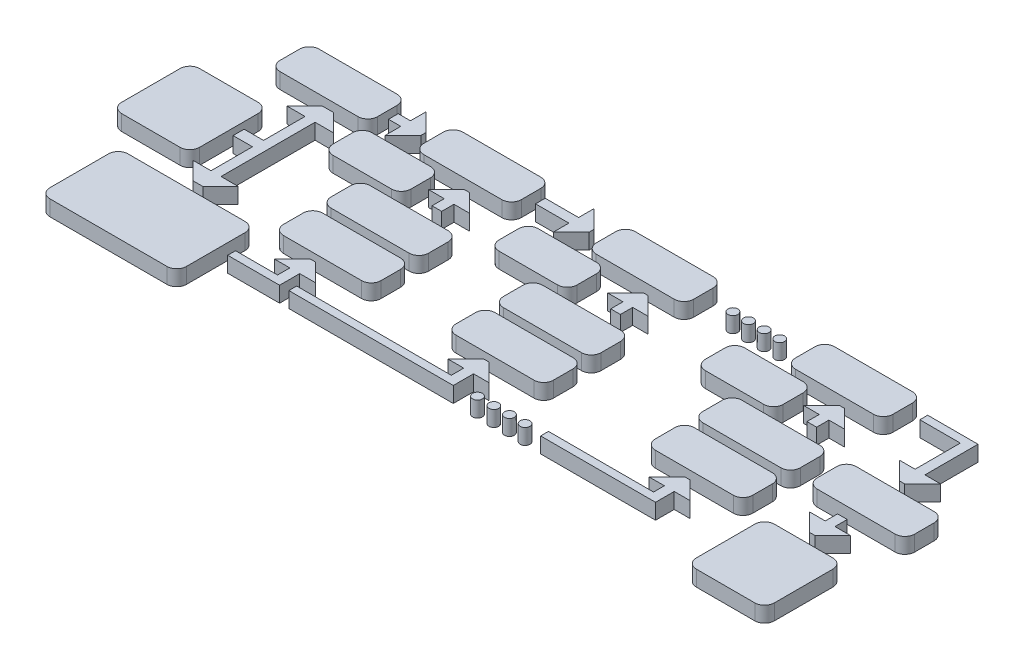
SolidWorks part; units mm, degrees
ref_plane "Front Plane" through (0, 0, 0) normal (0, 0, 1) x (1, 0, 0)
ref_plane "Top Plane" through (0, 0, 0) normal (0, 1, 0) x (1, 0, 0)
ref_plane "Right Plane" through (0, 0, 0) normal (1, 0, 0) x (0, 0, -1)
sketch "Sketch2" plane through (0, 0, 0) normal (0, 1, 0) x (1, 0, 0)
  line L0 (229.7637, 216.3988) -> (1504.4304, 216.3988) construction
  line L1 (-69.85, 25.4) -> (69.85, 25.4) construction
  line L2 (-69.85, 25.4) -> (-69.85, -25.4) construction
  line L3 (-69.85, -25.4) -> (69.85, -25.4) construction
  line L4 (69.85, 25.4) -> (69.85, -25.4) construction
  point P0 (0, 0)
  dimension "D1" = 50.8
  dimension "D2" = 139.7
sketch "Sketch3" plane through (0, 0, 0) normal (0, 1, 0) x (1, 0, 0)
  line L0 (-7.1378, 13.5425) -> (5.5622, 13.5425)
  line L1 (-58.6316, 13.5425) -> (-45.9316, 13.5425)
  line L2 (-60.2191, 15.13) -> (-60.2191, 18.305)
  line L3 (-58.6316, 19.8925) -> (-45.9316, 19.8925)
  line L4 (-44.3441, 15.13) -> (-44.3441, 18.305)
  line L5 (-8.7253, 15.13) -> (-8.7253, 18.305)
  line L6 (-7.1378, 19.8925) -> (5.5622, 19.8925)
  line L7 (7.1497, 15.13) -> (7.1497, 18.305)
  line L8 (-35.2189, 13.5425) -> (-22.5189, 13.5425)
  line L9 (-36.8064, 15.13) -> (-36.8064, 18.305)
  line L10 (-35.2189, 19.8925) -> (-22.5189, 19.8925)
  line L11 (-20.9314, 15.13) -> (-20.9314, 18.305)
  line L12 (-35.2189, -1.5522) -> (-22.5189, -1.5522)
  line L13 (-36.8064, 0.0353) -> (-36.8064, 3.2103)
  line L14 (-35.2189, 4.7978) -> (-22.5189, 4.7978)
  line L15 (-20.9314, 0.0353) -> (-20.9314, 3.2103)
  line L16 (25.3178, 13.5425) -> (38.0178, 13.5425)
  line L17 (23.7303, 15.13) -> (23.7303, 18.305)
  line L18 (25.3178, 19.8925) -> (38.0178, 19.8925)
  line L19 (39.6053, 15.13) -> (39.6053, 18.305)
  line L20 (-7.1378, -1.5522) -> (5.5622, -1.5522)
  line L21 (-8.7253, 0.0353) -> (-8.7253, 3.2103)
  line L22 (-7.1378, 4.7978) -> (5.5622, 4.7978)
  line L23 (7.1497, 0.0353) -> (7.1497, 3.2103)
  line L24 (25.3178, -1.5522) -> (38.0178, -1.5522)
  line L25 (23.7303, 0.0353) -> (23.7303, 3.2103)
  line L26 (25.3178, 4.7978) -> (38.0178, 4.7978)
  line L27 (39.6053, 0.0353) -> (39.6053, 3.2103)
  line L28 (43.9892, -1.5958) -> (56.6892, -1.5958)
  line L29 (42.4017, -0.0083) -> (42.4017, 3.1667)
  line L30 (43.9892, 4.7542) -> (56.6892, 4.7542)
  line L31 (58.2767, -0.0083) -> (58.2767, 3.1667)
  line L32 (-35.2189, -9.2939) -> (-22.5189, -9.2939)
  line L33 (-36.8064, -7.7064) -> (-36.8064, -4.5314)
  line L34 (-35.2189, -2.9439) -> (-22.5189, -2.9439)
  line L35 (-20.9314, -7.7064) -> (-20.9314, -4.5314)
  line L36 (-7.1378, -9.2939) -> (5.5622, -9.2939)
  line L37 (-8.7253, -7.7064) -> (-8.7253, -4.5314)
  line L38 (-7.1378, -2.9439) -> (5.5622, -2.9439)
  line L39 (7.1497, -7.7064) -> (7.1497, -4.5314)
  line L40 (25.3178, -9.2939) -> (38.0178, -9.2939)
  line L41 (23.7303, -7.7064) -> (23.7303, -4.5314)
  line L42 (25.3178, -2.9439) -> (38.0178, -2.9439)
  line L43 (39.6053, -7.7064) -> (39.6053, -4.5314)
  line L44 (-42.5202, 6.0577) -> (-32.9952, 6.0577)
  line L45 (-40.3627, -23.1396) -> (-59.4127, -23.1396)
  line L46 (-38.7752, -21.5521) -> (-38.7752, -12.0271)
  line L47 (-40.3627, -10.4396) -> (-59.4127, -10.4396)
  line L48 (-61.0002, -21.5521) -> (-61.0002, -12.0271)
  line L49 (-15.4735, 6.0577) -> (-5.9485, 6.0577)
  line L50 (-17.061, 7.6452) -> (-17.061, 10.8202)
  line L51 (-15.4735, 12.4077) -> (-5.9485, 12.4077)
  line L52 (-4.361, 7.6452) -> (-4.361, 10.8202)
  line L53 (-44.1077, 7.6452) -> (-44.1077, 10.8202)
  line L54 (-42.5202, 12.4077) -> (-32.9952, 12.4077)
  line L55 (-31.4077, 7.6452) -> (-31.4077, 10.8202)
  line L56 (18.1587, 6.0027) -> (27.6837, 6.0027)
  line L57 (16.5712, 7.5902) -> (16.5712, 10.8202)
  line L58 (18.1587, 12.4077) -> (27.6837, 12.4077)
  line L59 (29.2712, 7.5902) -> (29.2712, 10.8202)
  line L61 (45.4421, -22.7292) -> (54.9671, -22.7292)
  line L62 (43.8546, -21.1417) -> (43.8546, -11.6167)
  line L63 (45.4421, -10.0292) -> (54.9671, -10.0292)
  line L64 (56.5546, -21.1417) -> (56.5546, -11.6167)
  line L68 (-65.6185, -5.2757) -> (-56.0935, -5.2757)
  line L69 (-67.206, -3.6882) -> (-67.206, 5.8368)
  line L70 (-65.6185, 7.4243) -> (-56.0935, 7.4243)
  line L71 (-54.506, -3.6882) -> (-54.506, 5.8368)
  line L72 (-28.9233, -10.4275) -> (-26.0056, -13.3452)
  line L73 (-26.0056, -13.3452) -> (-28.5418, -13.3452)
  line L74 (-28.5418, -13.3452) -> (-28.5418, -16.6229)
  line L75 (-28.5418, -16.6229) -> (-36.9891, -16.6229)
  line L76 (-36.9891, -16.6229) -> (-36.9891, -15.3446)
  line L77 (-36.9891, -15.3446) -> (-30.1442, -15.3446)
  line L78 (-30.1442, -15.3446) -> (-30.1442, -13.3452)
  line L79 (-30.1442, -13.3452) -> (-32.6804, -13.3452)
  line L80 (-32.6804, -13.3452) -> (-29.7627, -10.4275)
  line L81 (-29.7627, -10.4275) -> (-28.9233, -10.4275)
  line L83 (-0.6361, -10.4031) -> (2.2816, -13.3208)
  line L84 (2.2816, -13.3208) -> (-0.2545, -13.3208)
  line L85 (-0.2545, -13.3208) -> (-0.2545, -16.6229)
  line L86 (-0.2545, -16.6229) -> (-27.0325, -16.6229)
  line L87 (-27.0325, -16.6229) -> (-27.0325, -15.3446)
  line L88 (-27.0325, -15.3446) -> (-1.857, -15.3446)
  line L89 (-1.857, -15.3446) -> (-1.857, -13.3208)
  line L90 (-1.857, -13.3208) -> (-4.3932, -13.3208)
  line L91 (-4.3932, -13.3208) -> (-1.4755, -10.4031)
  line L92 (-1.4755, -10.4031) -> (-0.6361, -10.4031)
  line L93 (-26.1405, 11.913) -> (-23.2228, 8.9953)
  line L94 (-23.2228, 8.9953) -> (-25.759, 8.9953)
  line L95 (-25.759, 8.9953) -> (-25.759, 6.9959)
  line L99 (-27.3352, 6.9959) -> (-27.3352, 8.9953)
  line L100 (-27.3352, 8.9953) -> (-29.8713, 8.9953)
  line L101 (-29.8713, 8.9953) -> (-26.9537, 11.913)
  line L102 (-26.9537, 11.913) -> (-26.1405, 11.913)
  line L103 (-27.3352, 6.9959) -> (-25.759, 6.9959)
  line L104 (2.9528, 11.9239) -> (5.8705, 9.0062)
  line L105 (5.8705, 9.0062) -> (3.3343, 9.0062)
  line L106 (3.3343, 9.0062) -> (3.3343, 7.0068)
  line L107 (1.7581, 7.0068) -> (1.7581, 9.0062)
  line L108 (1.7581, 9.0062) -> (-0.778, 9.0062)
  line L109 (-0.778, 9.0062) -> (2.1397, 11.9239)
  line L110 (2.1397, 11.9239) -> (2.9528, 11.9239)
  line L111 (1.7581, 7.0068) -> (3.3343, 7.0068)
  line L112 (-38.1588, 16.0347) -> (-41.0765, 13.1171)
  line L113 (-41.0765, 13.1171) -> (-41.0765, 15.6532)
  line L114 (-41.0765, 15.6532) -> (-43.0759, 15.6532)
  line L115 (-43.0759, 17.2294) -> (-41.0765, 17.2294)
  line L116 (-41.0765, 17.2294) -> (-41.0765, 19.7656)
  line L117 (-41.0765, 19.7656) -> (-38.1588, 16.8479)
  line L118 (-38.1588, 16.8479) -> (-38.1588, 16.0347)
  line L119 (-43.0759, 17.2294) -> (-43.0759, 15.6532)
  line L120 (-10.8232, 16.0784) -> (-13.7409, 13.1608)
  line L121 (-13.7409, 13.1608) -> (-13.7409, 15.6969)
  line L122 (-13.7409, 15.6969) -> (-19.1778, 15.6969)
  line L123 (-19.1778, 17.2731) -> (-13.7409, 17.2731)
  line L124 (-13.7409, 17.2731) -> (-13.7409, 19.8093)
  line L125 (-13.7409, 19.8093) -> (-10.8232, 16.8916)
  line L126 (-10.8232, 16.8916) -> (-10.8232, 16.0784)
  line L127 (-19.1778, 17.2731) -> (-19.1778, 15.6969)
  line L128 (-48.5485, 12.1317) -> (-45.6699, 9.2532)
  line L129 (-45.6699, 9.2532) -> (-48.6429, 9.2532)
  line L130 (-48.6429, 9.2532) -> (-48.6429, -6.061)
  line L132 (-53.4328, 0.6974) -> (-53.4328, 2.4948)
  line L133 (-53.4328, 2.4948) -> (-50.2727, 2.4948)
  line L134 (-50.2727, 2.4948) -> (-50.2727, 9.2532)
  line L135 (-50.2727, 9.2532) -> (-53.2457, 9.2532)
  line L136 (-53.2457, 9.2532) -> (-50.3672, 12.1317)
  line L137 (-50.3672, 12.1317) -> (-48.5485, 12.1317)
  line L138 (-50.3212, -8.9395) -> (-48.7365, -8.9395)
  line L139 (-53.1997, -6.061) -> (-50.3212, -8.9395)
  line L140 (-50.2727, -6.061) -> (-53.1997, -6.061)
  line L141 (-50.2727, 0.6974) -> (-50.2727, -6.061)
  line L142 (-45.8579, -6.061) -> (-48.6429, -6.061)
  line L143 (-48.7365, -8.9395) -> (-45.8579, -6.061)
  line L144 (-53.4328, 0.6974) -> (-50.2727, 0.6974)
  line L145 (32.3032, -10.6568) -> (35.2209, -13.5745)
  line L146 (35.2209, -13.5745) -> (32.6847, -13.5745)
  line L147 (32.6847, -13.5745) -> (32.6847, -16.6229)
  line L148 (32.6847, -16.6229) -> (13.9711, -16.6229)
  line L149 (13.9711, -16.6229) -> (13.9711, -15.3446)
  line L150 (13.9711, -15.3446) -> (31.0823, -15.3446)
  line L151 (31.0823, -15.3446) -> (31.0823, -13.5745)
  line L152 (31.0823, -13.5745) -> (28.5461, -13.5745)
  line L153 (28.5461, -13.5745) -> (31.4638, -10.6568)
  line L154 (31.4638, -10.6568) -> (32.3032, -10.6568)
  line L155 (-69.85, -25.4) -> (69.85, -25.4) construction
  line L156 (69.85, 25.4) -> (69.85, -25.4) construction
  line L157 (-69.85, 25.4) -> (69.85, 25.4) construction
  line L158 (-69.85, 25.4) -> (-69.85, -25.4) construction
  line L159 (-69.85, -25.4) -> (69.85, -25.4) construction
  line L160 (69.85, 25.4) -> (69.85, -25.4) construction
  line L161 (-69.85, 25.4) -> (69.85, 25.4) construction
  line L162 (-69.85, 25.4) -> (-69.85, -25.4) construction
  line L171 (49.4987, -8.3259) -> (46.6093, -5.4365)
  line L172 (46.6093, -5.4365) -> (49.1455, -5.4365)
  line L173 (49.1455, -5.4365) -> (49.1455, -3.4371)
  line L174 (50.7217, -3.4371) -> (50.7217, -5.4365)
  line L175 (50.7217, -5.4365) -> (53.2579, -5.4365)
  line L176 (53.2579, -5.4365) -> (50.3685, -8.3259)
  line L177 (50.3685, -8.3259) -> (49.4987, -8.3259)
  line L178 (50.7217, -3.4371) -> (49.1455, -3.4371)
  line L179 (34.8308, 12.0058) -> (37.7485, 9.0881)
  line L180 (37.7485, 9.0881) -> (35.2123, 9.0881)
  line L181 (35.2123, 9.0881) -> (35.2123, 7.0887)
  line L182 (33.6361, 7.0887) -> (33.6361, 9.0881)
  line L183 (33.6361, 9.0881) -> (31.0999, 9.0881)
  line L184 (31.0999, 9.0881) -> (34.0176, 12.0058)
  line L185 (34.0176, 12.0058) -> (34.8308, 12.0058)
  line L186 (33.6361, 7.0887) -> (35.2123, 7.0887)
  line L190 (50.761, 17.8203) -> (42.5688, 17.8203)
  line L197 (49.54, 6.2582) -> (50.3795, 6.2582)
  line L198 (46.6223, 9.1759) -> (49.54, 6.2582)
  line L199 (49.1585, 9.1759) -> (46.6223, 9.1759)
  line L200 (49.1585, 16.542) -> (49.1585, 9.1759)
  line L201 (42.5688, 16.542) -> (49.1585, 16.542)
  line L202 (42.5688, 17.8203) -> (42.5688, 16.542)
  line L203 (50.761, 9.1759) -> (50.761, 17.8203)
  line L204 (53.2972, 9.1759) -> (50.761, 9.1759)
  line L205 (50.3795, 6.2582) -> (53.2972, 9.1759)
  arc A0 (-58.6316, 13.5425) -> (-60.2191, 15.13) centre (-58.6316, 15.13) cw
  arc A1 (-45.9316, 13.5425) -> (-44.3441, 15.13) centre (-45.9316, 15.13) ccw
  arc A2 (-45.9316, 19.8925) -> (-44.3441, 18.305) centre (-45.9316, 18.305) cw
  arc A3 (-60.2191, 18.305) -> (-58.6316, 19.8925) centre (-58.6316, 18.305) cw
  arc A4 (-7.1378, 13.5425) -> (-8.7253, 15.13) centre (-7.1378, 15.13) cw
  arc A5 (5.5622, 13.5425) -> (7.1497, 15.13) centre (5.5622, 15.13) ccw
  arc A6 (5.5622, 19.8925) -> (7.1497, 18.305) centre (5.5622, 18.305) cw
  arc A7 (-8.7253, 18.305) -> (-7.1378, 19.8925) centre (-7.1378, 18.305) cw
  arc A8 (-35.2189, 13.5425) -> (-36.8064, 15.13) centre (-35.2189, 15.13) cw
  arc A9 (-22.5189, 13.5425) -> (-20.9314, 15.13) centre (-22.5189, 15.13) ccw
  arc A10 (-22.5189, 19.8925) -> (-20.9314, 18.305) centre (-22.5189, 18.305) cw
  arc A11 (-36.8064, 18.305) -> (-35.2189, 19.8925) centre (-35.2189, 18.305) cw
  arc A12 (-35.2189, -1.5522) -> (-36.8064, 0.0353) centre (-35.2189, 0.0353) cw
  arc A13 (-22.5189, -1.5522) -> (-20.9314, 0.0353) centre (-22.5189, 0.0353) ccw
  arc A14 (-22.5189, 4.7978) -> (-20.9314, 3.2103) centre (-22.5189, 3.2103) cw
  arc A15 (-36.8064, 3.2103) -> (-35.2189, 4.7978) centre (-35.2189, 3.2103) cw
  arc A16 (25.3178, 13.5425) -> (23.7303, 15.13) centre (25.3178, 15.13) cw
  arc A17 (38.0178, 13.5425) -> (39.6053, 15.13) centre (38.0178, 15.13) ccw
  arc A18 (38.0178, 19.8925) -> (39.6053, 18.305) centre (38.0178, 18.305) cw
  arc A19 (23.7303, 18.305) -> (25.3178, 19.8925) centre (25.3178, 18.305) cw
  arc A20 (-7.1378, -1.5522) -> (-8.7253, 0.0353) centre (-7.1378, 0.0353) cw
  arc A21 (5.5622, -1.5522) -> (7.1497, 0.0353) centre (5.5622, 0.0353) ccw
  arc A22 (5.5622, 4.7978) -> (7.1497, 3.2103) centre (5.5622, 3.2103) cw
  arc A23 (-8.7253, 3.2103) -> (-7.1378, 4.7978) centre (-7.1378, 3.2103) cw
  arc A24 (25.3178, -1.5522) -> (23.7303, 0.0353) centre (25.3178, 0.0353) cw
  arc A25 (38.0178, -1.5522) -> (39.6053, 0.0353) centre (38.0178, 0.0353) ccw
  arc A26 (38.0178, 4.7978) -> (39.6053, 3.2103) centre (38.0178, 3.2103) cw
  arc A27 (23.7303, 3.2103) -> (25.3178, 4.7978) centre (25.3178, 3.2103) cw
  arc A28 (43.9892, -1.5958) -> (42.4017, -0.0083) centre (43.9892, -0.0083) cw
  arc A29 (56.6892, -1.5958) -> (58.2767, -0.0083) centre (56.6892, -0.0083) ccw
  arc A30 (56.6892, 4.7542) -> (58.2767, 3.1667) centre (56.6892, 3.1667) cw
  arc A31 (42.4017, 3.1667) -> (43.9892, 4.7542) centre (43.9892, 3.1667) cw
  arc A32 (-35.2189, -9.2939) -> (-36.8064, -7.7064) centre (-35.2189, -7.7064) cw
  arc A33 (-22.5189, -9.2939) -> (-20.9314, -7.7064) centre (-22.5189, -7.7064) ccw
  arc A34 (-22.5189, -2.9439) -> (-20.9314, -4.5314) centre (-22.5189, -4.5314) cw
  arc A35 (-36.8064, -4.5314) -> (-35.2189, -2.9439) centre (-35.2189, -4.5314) cw
  arc A36 (-7.1378, -9.2939) -> (-8.7253, -7.7064) centre (-7.1378, -7.7064) cw
  arc A37 (5.5622, -9.2939) -> (7.1497, -7.7064) centre (5.5622, -7.7064) ccw
  arc A38 (5.5622, -2.9439) -> (7.1497, -4.5314) centre (5.5622, -4.5314) cw
  arc A39 (-8.7253, -4.5314) -> (-7.1378, -2.9439) centre (-7.1378, -4.5314) cw
  arc A40 (25.3178, -9.2939) -> (23.7303, -7.7064) centre (25.3178, -7.7064) cw
  arc A41 (38.0178, -9.2939) -> (39.6053, -7.7064) centre (38.0178, -7.7064) ccw
  arc A42 (38.0178, -2.9439) -> (39.6053, -4.5314) centre (38.0178, -4.5314) cw
  arc A43 (23.7303, -4.5314) -> (25.3178, -2.9439) centre (25.3178, -4.5314) cw
  arc A44 (-59.4127, -23.1396) -> (-61.0002, -21.5521) centre (-59.4127, -21.5521) cw
  arc A45 (-40.3627, -23.1396) -> (-38.7752, -21.5521) centre (-40.3627, -21.5521) ccw
  arc A46 (-38.7752, -12.0271) -> (-40.3627, -10.4396) centre (-40.3627, -12.0271) ccw
  arc A47 (-59.4127, -10.4396) -> (-61.0002, -12.0271) centre (-59.4127, -12.0271) ccw
  circle A48 centre (12.1126, 16.5536) radius 0.7937
  circle A49 centre (14.6526, 16.5536) radius 0.7937
  circle A50 centre (17.1926, 16.5536) radius 0.7937
  circle A51 centre (19.7326, 16.5536) radius 0.7937
  circle A52 centre (3.2182, -16.148) radius 0.7937
  circle A53 centre (5.8798, -16.148) radius 0.7937
  circle A54 centre (8.4198, -16.148) radius 0.7937
  circle A55 centre (10.9598, -16.148) radius 0.7937
  arc A56 (-15.4735, 6.0577) -> (-17.061, 7.6452) centre (-15.4735, 7.6452) cw
  arc A57 (-5.9485, 6.0577) -> (-4.361, 7.6452) centre (-5.9485, 7.6452) ccw
  arc A58 (-5.9485, 12.4077) -> (-4.361, 10.8202) centre (-5.9485, 10.8202) cw
  arc A59 (-17.061, 10.8202) -> (-15.4735, 12.4077) centre (-15.4735, 10.8202) cw
  arc A60 (-42.5202, 6.0577) -> (-44.1077, 7.6452) centre (-42.5202, 7.6452) cw
  arc A61 (-32.9952, 6.0577) -> (-31.4077, 7.6452) centre (-32.9952, 7.6452) ccw
  arc A62 (-32.9952, 12.4077) -> (-31.4077, 10.8202) centre (-32.9952, 10.8202) cw
  arc A63 (-44.1077, 10.8202) -> (-42.5202, 12.4077) centre (-42.5202, 10.8202) cw
  arc A64 (18.1587, 6.0027) -> (16.5712, 7.5902) centre (18.1587, 7.5902) cw
  arc A65 (27.6837, 6.0027) -> (29.2712, 7.5902) centre (27.6837, 7.5902) ccw
  arc A66 (27.6837, 12.4077) -> (29.2712, 10.8202) centre (27.6837, 10.8202) cw
  arc A67 (16.5712, 10.8202) -> (18.1587, 12.4077) centre (18.1587, 10.8202) cw
  arc A68 (54.9671, -10.0292) -> (56.5546, -11.6167) centre (54.9671, -11.6167) cw
  arc A69 (54.9671, -22.7292) -> (56.5546, -21.1417) centre (54.9671, -21.1417) ccw
  arc A70 (45.4421, -22.7292) -> (43.8546, -21.1417) centre (45.4421, -21.1417) cw
  arc A71 (43.8546, -11.6167) -> (45.4421, -10.0292) centre (45.4421, -11.6167) cw
  arc A76 (-56.0935, 7.4243) -> (-54.506, 5.8368) centre (-56.0935, 5.8368) cw
  arc A77 (-56.0935, -5.2757) -> (-54.506, -3.6882) centre (-56.0935, -3.6882) ccw
  arc A78 (-65.6185, -5.2757) -> (-67.206, -3.6882) centre (-65.6185, -3.6882) cw
  arc A79 (-67.206, 5.8368) -> (-65.6185, 7.4243) centre (-65.6185, 5.8368) cw
  point P6 (-60.2191, 13.5425)
  point P11 (-44.3441, 19.8925)
  point P14 (-60.2191, 19.8925)
  point P141 (-61.0002, -23.1396)
  point P144 (-38.7752, -23.1396)
  point P149 (-61.0002, -10.4396)
  point P168 (-17.061, 6.0577)
  point P172 (-4.361, 6.0577)
  point P180 (-17.061, 12.4077)
  point P211 (56.5546, -10.0292)
  point P216 (43.8546, -22.7292)
  point P219 (43.8546, -10.0292)
  dimension "D3" = 1.5875
  dimension "D4" = 1.5875
  dimension "D7" = 1.5875
  dimension "D8" = 1.5875
  dimension "D9" = 4
  dimension "D10" = 1.5875
  dimension "D13" = 1.5875
  dimension "D16" = 1.5875
  dimension "D1" = 6.35
  dimension "D2" = 15.875
  dimension "D5" = 12.7
  dimension "D6" = 22.225
  dimension "D11" = 6.35
  dimension "D12" = 12.7
  dimension "D14" = 12.7
  dimension "D15" = 12.7
extrude "Boss-Extrude1" add sketch "Sketch3" along normal blind 2.54
